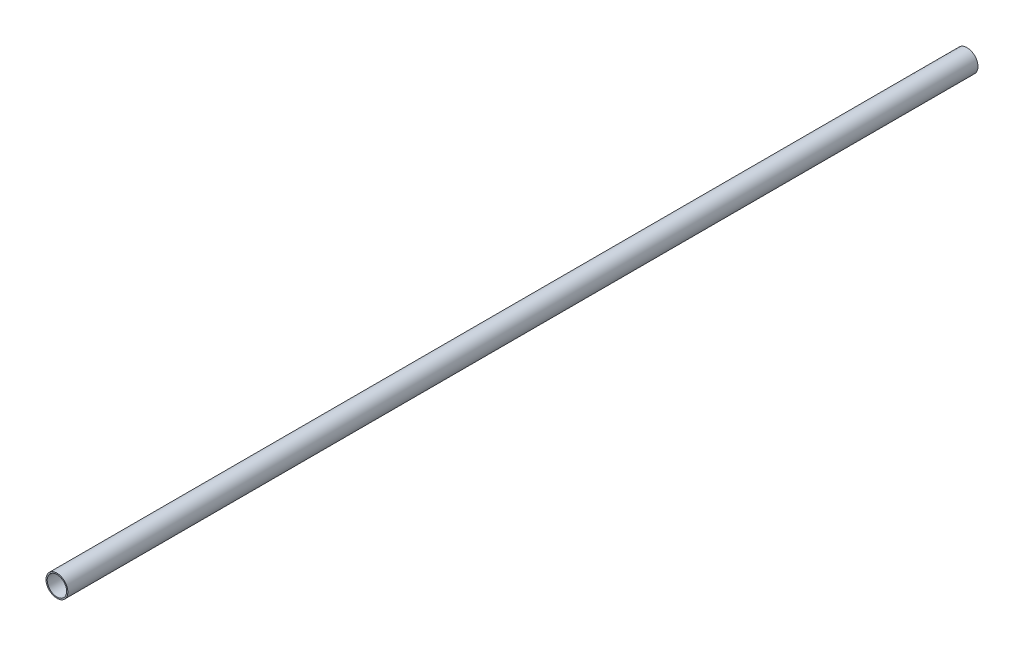
SolidWorks part; units mm, degrees
material "AISI 4130 Steel, annealed at 865C"
ref_plane "Front Plane" through (0, 0, 0) normal (0, 0, 1) x (1, 0, 0)
ref_plane "Top Plane" through (0, 0, 0) normal (0, 1, 0) x (1, 0, 0)
ref_plane "Right Plane" through (0, 0, 0) normal (1, 0, 0) x (0, 0, -1)
sketch "Sketch1" plane through (0, 0, 0) normal (0, 0, 1) x (1, 0, 0)
  circle A0 centre (0, 0) radius 7.0485
  circle A1 centre (0, 0) radius 7.9375
  dimension "D1" = 15.875
  dimension "D2" = 0.889
extrude "Boss-Extrude1" add sketch "Sketch1" along normal mid plane 660.4
